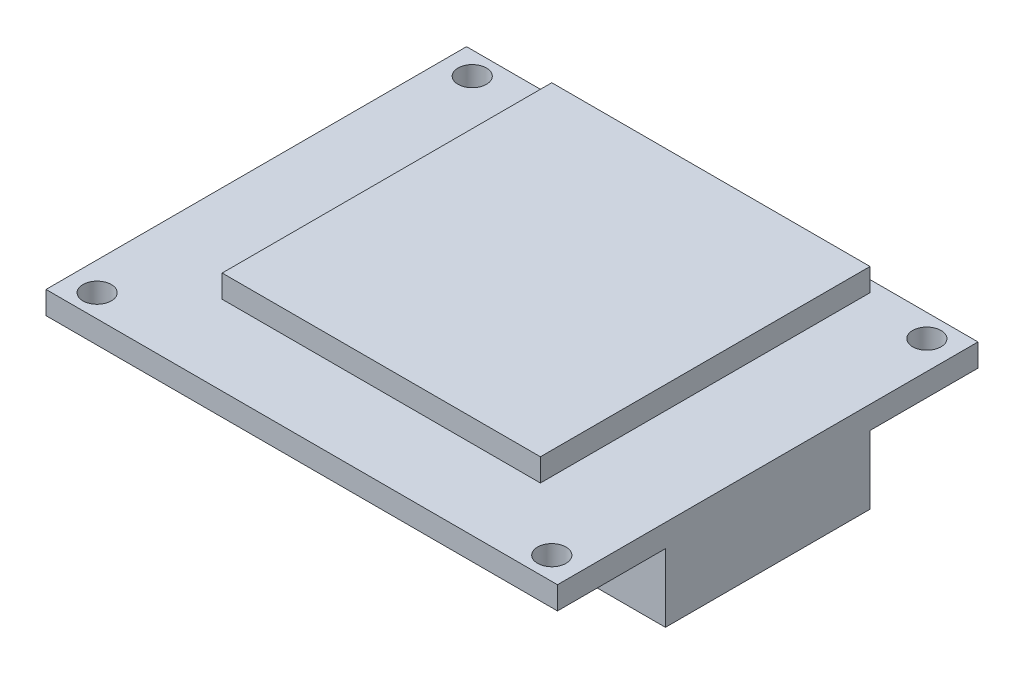
SolidWorks part; units mm, degrees
ref_plane "前视基准面" through (0, 0, 0) normal (0, 0, 1) x (1, 0, 0)
ref_plane "上视基准面" through (0, 0, 0) normal (0, 1, 0) x (1, 0, 0)
ref_plane "右视基准面" through (0, 0, 0) normal (1, 0, 0) x (0, 0, -1)
sketch "草图1" plane through (0, 0, 0) normal (0, 1, 0) x (1, 0, 0)
  line L1 (0, 0) -> (45, 0)
  line L2 (0, 0) -> (0, 37)
  line L3 (0, 37) -> (45, 37)
  line L4 (45, 0) -> (45, 37)
  dimension "D1" = 45
  dimension "D2" = 37
extrude "凸台-拉伸1" add sketch "草图1" along normal blind 2
sketch "草图2" plane through (0, 2, 0) normal (0, 1, 0) x (1, 0, 0)
  line L0 (22.5, 37) -> (22.5, 0) construction
  line L1 (45, 37) -> (0, 37) construction
  line L2 (0, 0) -> (45, 0) construction
  line L3 (36.5, 36) -> (8.5, 36)
  line L4 (8.5, 36) -> (8.5, 7)
  line L5 (8.5, 7) -> (36.5, 7)
  line L6 (36.5, 36) -> (36.5, 7)
  point P11 (22.5, 7)
  point P12 (22.5, 36)
  dimension "D1" = 29
  dimension "D2" = 1
  dimension "D3" = 14
extrude "凸台-拉伸2" add sketch "草图2" along normal blind 2
sketch "草图3" plane through (0, 2, 0) normal (0, 1, 0) x (1, 0, 0)
  line L0 (22.5, 37) -> (22.5, -7.9122) construction
  line L1 (45, 37) -> (0, 37) construction
  line L2 (0, 18.5) -> (53.2767, 18.5) construction
  line L3 (0, 37) -> (0, 0) construction
  circle A0 centre (2.5, 35) radius 1.25
  circle A1 centre (42.5, 35) radius 1.25
  circle A2 centre (42.5, 2) radius 1.25
  circle A3 centre (2.5, 2) radius 1.25
  dimension "D1" = 40
  dimension "D2" = 2.5
  dimension "D3" = 33
extrude "切除-拉伸1" cut sketch "草图3" against normal blind 2
sketch "草图4" plane through (0, 0, 0) normal (0, -1, 0) x (1, 0, 0)
  line L0 (45, 0) -> (45, -37) construction
  line L2 (37, -9.5) -> (37, -27.5)
  line L3 (37, -27.5) -> (45, -27.5)
  line L4 (45, -9.5) -> (45, -27.5)
  line L5 (0, -18.5) -> (52.8781, -18.5) construction
  line L6 (0, -37) -> (0, 0) construction
  line L7 (37, -9.5) -> (45, -9.5)
  point P11 (45, -18.5)
  point P12 (37, -18.5)
  dimension "D1" = 18
  dimension "D2" = 8
extrude "凸台-拉伸3" add sketch "草图4" along normal blind 6
